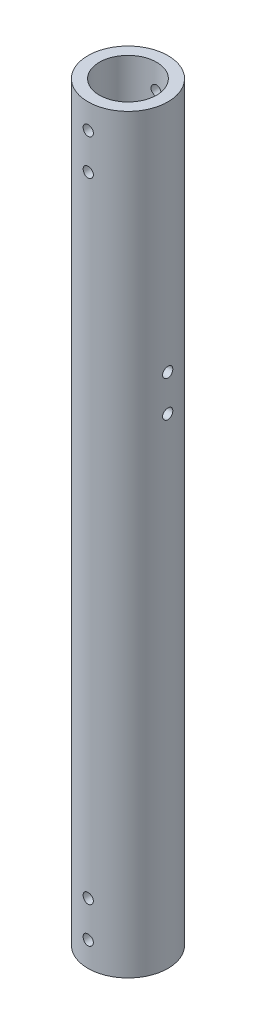
SolidWorks part; units mm, degrees
material "PVC Rigid"
ref_plane "Front Plane" through (0, 0, 0) normal (0, 0, 1) x (1, 0, 0)
ref_plane "Top Plane" through (0, 0, 0) normal (0, 1, 0) x (1, 0, 0)
ref_plane "Right Plane" through (0, 0, 0) normal (1, 0, 0) x (0, 0, -1)
sketch "Sketch1" plane through (0, 0, 0) normal (0, 1, 0) x (1, 0, 0)
  circle A0 centre (0, 0) radius 13.335
  circle A1 centre (0, 0) radius 9.525
  dimension "D1" = 26.67
  dimension "D2" = 19.05
extrude "Boss-Extrude1" add sketch "Sketch1" along normal blind 250
sketch "Sketch4" plane through (0, 0, 0) normal (0, 0, 1) x (1, 0, 0)
  line L0 (0, 250) -> (0, 229.7442) construction
  line L2 (13.335, 250) -> (-13.335, 250) construction
  line L3 (9.525, 250) -> (-9.525, 250) construction
  circle A0 centre (0, 241.7442) radius 1.7
  circle A1 centre (0, 229.7442) radius 1.7
  circle A3 centre (0, 229.7442) radius 1.7 construction
  dimension "D1" = 3.4
  dimension "D2" = 3.4
  dimension "D3" = 8.2558
  dimension "D4" = 12
extrude "Cut-Extrude1" cut sketch "Sketch4" against normal through all both and the other way through all
sketch "Sketch6" plane through (0, 0, 0) normal (0, 0, 1) x (1, 0, 0)
  line L0 (13.335, 250) -> (13.335, 0) construction
  line L1 (13.335, 250) -> (-13.335, 250) construction
  line L2 (-13.335, 0) -> (13.335, 0) construction
  line L3 (13.335, 125) -> (-13.335, 125) construction
  line L4 (-13.335, 250) -> (-13.335, 0) construction
  line L5 (13.335, 0) -> (13.335, 250) construction
ref_plane "Plane2" through (0, 125, 0) normal (0, 1, 0) x (1, 0, 0)
mirror "Mirror2" about plane through (0, 125, 0) normal (0, 1, 0) of "Cut-Extrude1"
sketch "Sketch7" plane through (0, 0, 0) normal (1, 0, 0) x (0, 0, -1)
  line L0 (0, 250) -> (0, 0) construction
  line L1 (13.335, 250) -> (-13.335, 250) construction
  circle A2 centre (0, 160.0058) radius 1.7
  circle A3 centre (0, 172.0058) radius 1.7
  point P1 (0, 0)
  point P7 (0, 0)
  point P8 (0, 0)
  point P10 (0, 0)
  dimension "D1" = 3.4
  dimension "D2" = 3.4
  dimension "D3" = 12
  dimension "D4" = 77.9942
extrude "Cut-Extrude2" cut sketch "Sketch7" against normal through all both and the other way through all
